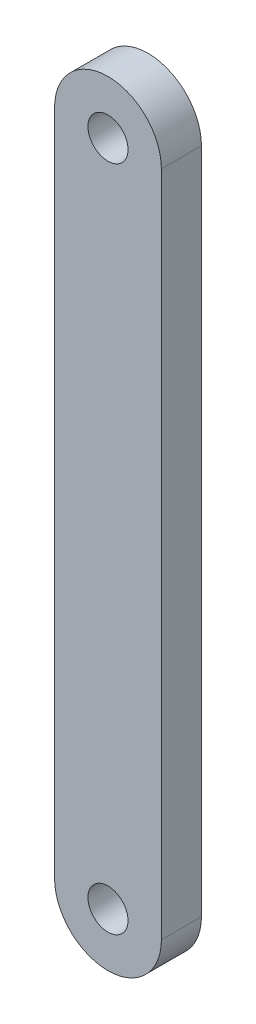
SolidWorks part; units mm, degrees
ref_plane "Alzado" through (0, 0, 0) normal (0, 0, 1) x (1, 0, 0)
ref_plane "Planta" through (0, 0, 0) normal (0, 1, 0) x (1, 0, 0)
ref_plane "Vista lateral" through (0, 0, 0) normal (1, 0, 0) x (0, 0, -1)
sketch "Croquis1" plane through (0, 0, 0) normal (0, 0, 1) x (1, 0, 0)
  line L0 (0, 25) -> (0, -25) construction
  line L1 (4, 25) -> (4, -25)
  line L2 (-4, 25) -> (-4, -25)
  arc A0 (4, 25) -> (-4, 25) centre (0, 25) ccw
  arc A1 (-4, -25) -> (4, -25) centre (0, -25) ccw
  circle A2 centre (0, -25) radius 1.5
  circle A3 centre (0, 25) radius 1.5
  point P3 (0, 0)
  point P12 (0, 0)
  dimension "D1" = 4
  dimension "D3" = 3
  dimension "D4" = 3
  dimension "D2" = 50
extrude "Saliente-Extruir1" add sketch "Croquis1" along normal blind 3
